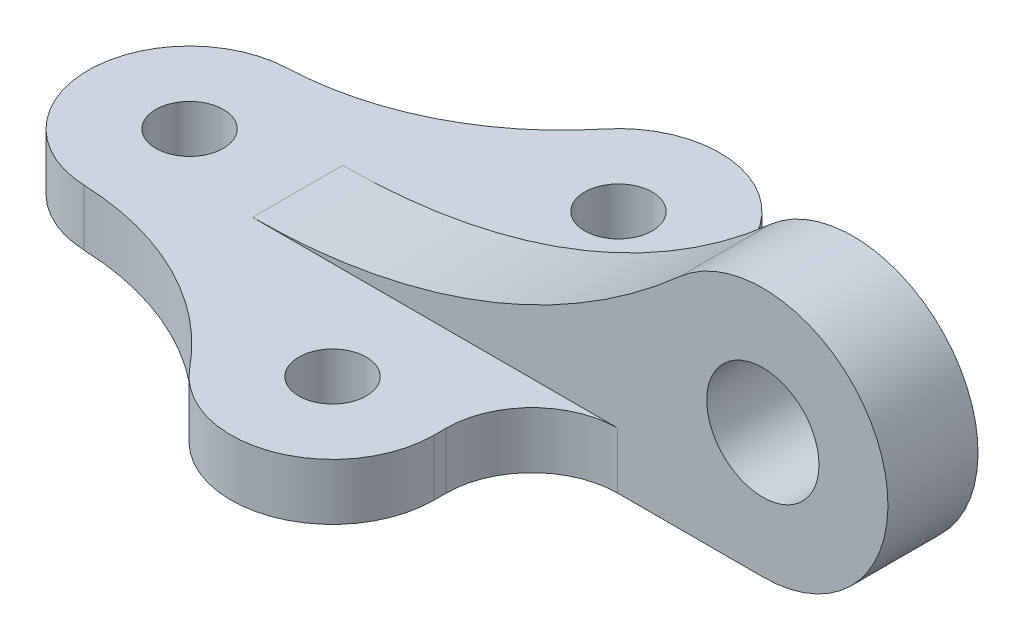
SolidWorks part; units mm, degrees
ref_plane "Front Plane" through (0, 0, 0) normal (0, 0, 1) x (1, 0, 0)
ref_plane "Top Plane" through (0, 0, 0) normal (0, 1, 0) x (1, 0, 0)
ref_plane "Right Plane" through (0, 0, 0) normal (1, 0, 0) x (0, 0, -1)
sketch "Sketch2" plane through (0, 0, 0) normal (0, 1, 0) x (1, 0, 0)
  line L0 (0, 0) -> (90.1764, 0) construction
  line L1 (68.834, 25.4) -> (68.834, -25.4)
  circle A0 centre (0, 0) radius 5.9944
  circle A1 centre (50.8, 25.4) radius 5.9944
  circle A2 centre (50.8, -25.4) radius 5.9944
  arc A3 (-0.6921, 18.0207) -> (-0.6921, -18.0207) centre (0, 0) ccw
  arc A4 (36.7987, -36.7661) -> (68.834, -25.4) centre (50.8, -25.4) ccw
  arc A5 (68.834, 25.4) -> (36.7987, 36.7661) centre (50.8, 25.4) ccw
  arc A6 (-0.6921, -18.0207) -> (36.7987, -36.7661) centre (-2.6416, -68.7833) cw
  arc A7 (-0.6921, 18.0207) -> (36.7987, 36.7661) centre (-2.6416, 68.7833) ccw
  dimension "D1" = 11.9888
  dimension "D4" = 36.068
  dimension "D5" = 50.8
  dimension "D2" = 50.8
  dimension "D3" = 50.8
extrude "Boss-Extrude1" add sketch "Sketch2" along normal mid plane 10.0076
sketch "Sketch3" plane through (0, 0, 0) normal (0, 0, 1) x (1, 0, 0)
  line L0 (109.855, -5.0038) -> (68.834, -5.0038)
  line L1 (36.7987, -5.0038) -> (68.834, -5.0038) construction
  line L2 (36.7987, 5.0038) -> (-0.6921, 5.0038) construction
  line L3 (68.834, 5.0038) -> (68.834, -5.0038) construction
  line L4 (68.834, 5.0038) -> (68.834, -5.0038)
  line L5 (68.834, 5.0038) -> (36.7987, 5.0038) construction
  line L6 (36.7987, 5.0038) -> (19.2006, 5.0038)
  line L7 (68.834, 5.0038) -> (36.7987, 5.0038)
  circle A0 centre (109.855, 17.2212) radius 9.9695
  arc A1 (109.855, -5.0038) -> (95.0973, 33.8393) centre (109.855, 17.2212) ccw
  arc A2 (19.2006, 5.0038) -> (95.0973, 33.8393) centre (19.2006, 119.3038) ccw
  dimension "D1" = 19.939
  dimension "D2" = 44.45
  dimension "D4" = 114.3
  dimension "D3" = 109.855
extrude "Boss-Extrude2" add sketch "Sketch3" along normal mid plane 16.002
fillet "Fillet1" radius 15.24 2 edges at (68.834, 0, -8.001) (68.834, 0, 8.001)
